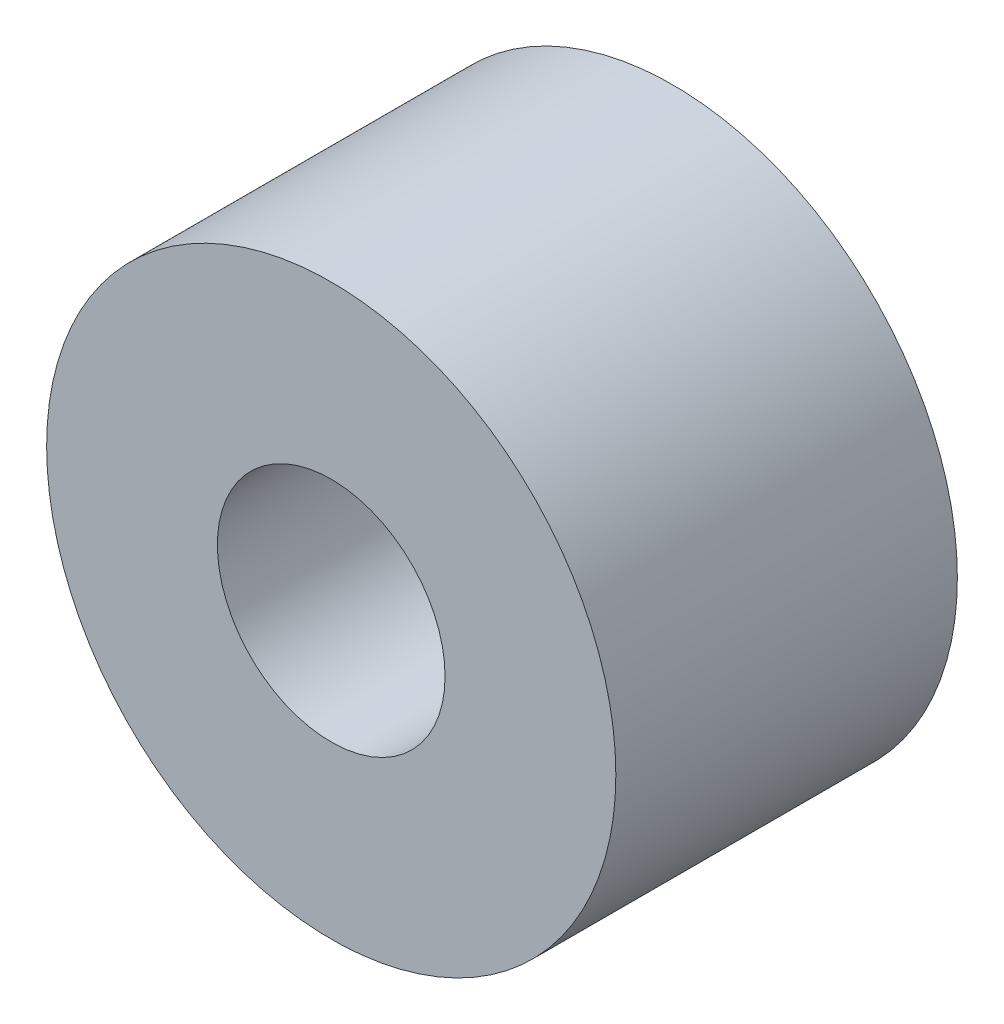
SolidWorks part; units mm, degrees
ref_plane "Front Plane" through (0, 0, 0) normal (0, 0, 1) x (1, 0, 0)
ref_plane "Top Plane" through (0, 0, 0) normal (0, 1, 0) x (1, 0, 0)
ref_plane "Right Plane" through (0, 0, 0) normal (1, 0, 0) x (0, 0, -1)
sketch "Sketch1" plane through (0, 0, 0) normal (0, 0, 1) x (1, 0, 0)
  circle A0 centre (0, 0) radius 1
  circle A1 centre (0, 0) radius 2.5
  dimension "D1" = 2
  dimension "D2" = 5
extrude "Boss-Extrude1" add sketch "Sketch1" along normal blind 3
equation "\"emitting_window_width\"=63mm"
equation "\"emitting_window_height\"=48mm"
equation "\"emitter_mounting_peg_diameter\"=3.4mm"
equation "\"emitter_wall_clearance\"=0.5mm"
equation "\"wall_thickness\"=2mm"
equation "\"ballast_pcb_length\"=88.9mm"
equation "\"ballast_pcb_width\"=88.9mm"
equation "\"ballast_pcb_clearance\"=0.3mm"
equation "\"emitter_balast_separation\"=8mm"
equation "\"emitter_ballast_spacer_clearance\"=0.2mm"
equation "\"edge_radius\"=5mm"
equation "\"grille_slot_width\"=2mm"
equation "\"grille_slot_length\"=3.5mm"
equation "\"grille_spacing\"=6.3mm"
equation "\"hoop_inside_width\"=75.9mm"
equation "\"hoop_inside_height\"=65mm"
equation "\"hoop_thickness\"=8mm"
equation "\"hoop_width\"=6mm"
equation "\"hoop_corner_radius\"=10mm"
equation "\"hoop_roundover_radius\"=1mm"
equation "\"hoop_inner_outer_clearance\"=0.05mm"
equation "\"hoop_slot_clearance\"=0.5mm"
equation "\"hoop_dowel_pin_interference_diameter\"=2mm"
equation "\"diffuser_film_thickness\"=0.001in"
equation "\"hoop_ring_magnet_inner_diameter\"=2mm"
equation "\"hoop_ring_magnet_outer_diameter\"=5mm"
equation "\"hoop_ring_magnet_thickness\"=3mm"
equation "\"D1@Sketch1\"=\"hoop_ring_magnet_inner_diameter\""
equation "\"D2@Sketch1\"=\"hoop_ring_magnet_outer_diameter\""
equation "\"D1@Boss-Extrude1\"=\"hoop_ring_magnet_thickness\""
